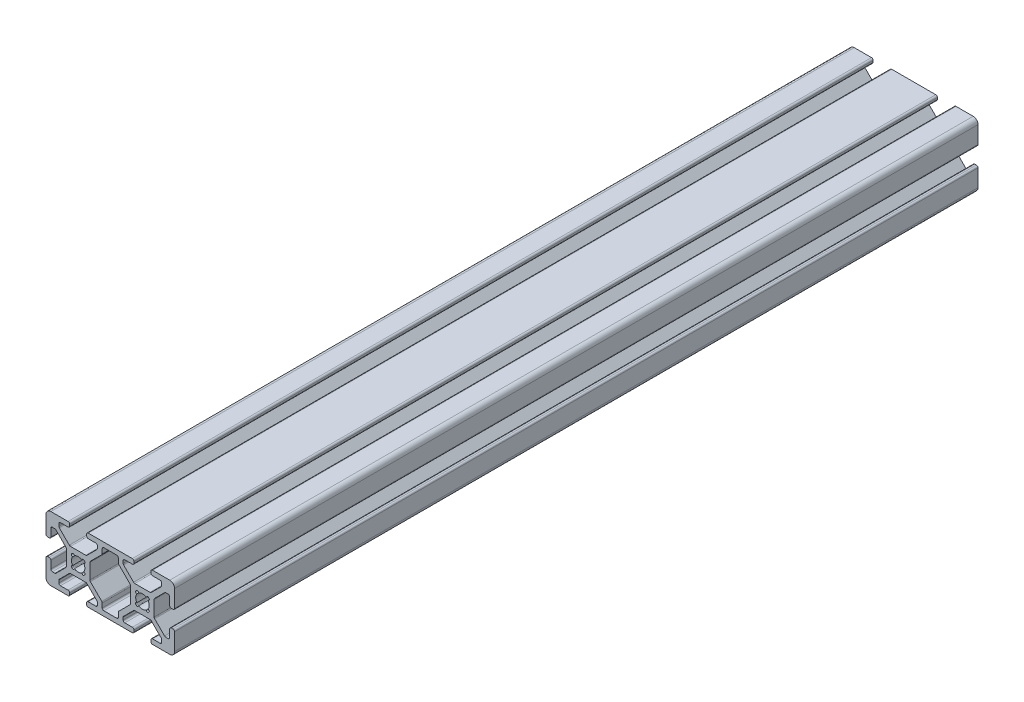
SolidWorks part; units mm, degrees
material "6061-T6 (SS)"
ref_plane "Front Plane" through (0, 0, 0) normal (0, 0, 1) x (1, 0, 0)
ref_plane "Top Plane" through (0, 0, 0) normal (0, 1, 0) x (1, 0, 0)
ref_plane "Right Plane" through (0, 0, 0) normal (1, 0, 0) x (0, 0, -1)
sketch "Sketch1" plane through (0, 0, 0) normal (0, 0, 1) x (1, 0, 0)
  line L0 (-20, 8.5) -> (-20, 3.138)
  line L1 (-19.492, 2.63) -> (-19.008, 2.63)
  line L2 (-18.5, 3.138) -> (-18.5, 5.487)
  line L3 (-17.992, 5.995) -> (-17.2661, 5.995)
  line L4 (-16.9069, 5.8462) -> (-13.8038, 2.7431)
  line L5 (-13.655, 2.3839) -> (-13.655, -2.3839)
  line L6 (-18.5, 10) -> (-13.138, 10)
  line L7 (-12.63, 9.492) -> (-12.63, 9.008)
  line L8 (-13.138, 8.5) -> (-15.487, 8.5)
  line L9 (-15.995, 7.992) -> (-15.995, 7.2661)
  line L10 (-15.8462, 6.9069) -> (-12.7431, 3.8038)
  line L11 (-12.3839, 3.655) -> (-7.6161, 3.655)
  line L12 (-20, 10) -> (-10, 0) construction
  line L13 (-10, 0) -> (-6.345, 0) construction
  line L14 (-13.655, 0) -> (-10, 0) construction
  line L15 (-10, -3.655) -> (-10, 0) construction
  line L16 (-11.7504, 1.5704) -> (-11.5704, 1.7504) construction
  line L17 (-12.0287, 1.8487) -> (-11.8487, 2.0287)
  line L18 (-16.9069, 5.8462) -> (-15.8462, 6.9069) construction
  line L19 (-7.9713, 1.8487) -> (-8.1513, 2.0287)
  line L20 (-7.37, 9.492) -> (-7.37, 9.008)
  line L21 (-6.862, 8.5) -> (-4.513, 8.5)
  line L22 (-4.005, 7.992) -> (-4.005, 7.2661)
  line L23 (-4.1538, 6.9069) -> (-7.2569, 3.8038)
  line L24 (-6.862, 10) -> (6.862, 10)
  line L25 (0, 10) -> (0, -10) construction
  line L26 (1.997, 8.5) -> (-1.997, 8.5)
  line L27 (-2.505, 7.992) -> (-2.505, 6.6448)
  line L28 (-2.6538, 6.2856) -> (-6.1962, 2.7431)
  line L29 (-6.345, 2.3839) -> (-6.345, -2.3839)
  line L30 (-6.345, 0) -> (6.345, 0) construction
  line L31 (-4.005, 7.629) -> (-2.505, 7.629) construction
  line L32 (-5.7053, 5.3553) -> (-4.6447, 4.2947) construction
  line L33 (5.7053, 5.3553) -> (4.6447, 4.2947) construction
  line L34 (4.005, 7.629) -> (2.505, 7.629) construction
  line L35 (16.9069, 5.8462) -> (15.8462, 6.9069) construction
  line L36 (11.7504, 1.5704) -> (11.5704, 1.7504) construction
  line L37 (10, -3.655) -> (10, 3.655) construction
  line L38 (13.655, 0) -> (10, 0) construction
  line L39 (10, 0) -> (6.345, 0) construction
  line L40 (20, 10) -> (10, 0) construction
  line L41 (6.345, 2.3839) -> (6.345, -2.3839)
  line L42 (2.6538, 6.2856) -> (6.1962, 2.7431)
  line L43 (2.505, 7.992) -> (2.505, 6.6448)
  line L44 (4.1538, 6.9069) -> (7.2569, 3.8038)
  line L45 (4.005, 7.992) -> (4.005, 7.2661)
  line L46 (6.862, 8.5) -> (4.513, 8.5)
  line L47 (7.37, 9.492) -> (7.37, 9.008)
  line L48 (7.9713, 1.8487) -> (8.1513, 2.0287)
  line L49 (12.0287, 1.8487) -> (11.8487, 2.0287)
  line L50 (12.3839, 3.655) -> (7.6161, 3.655)
  line L51 (15.8462, 6.9069) -> (12.7431, 3.8038)
  line L52 (15.995, 7.992) -> (15.995, 7.2661)
  line L53 (13.138, 8.5) -> (15.487, 8.5)
  line L54 (12.63, 9.492) -> (12.63, 9.008)
  line L55 (18.5, 10) -> (13.138, 10)
  line L56 (13.655, 2.3839) -> (13.655, -2.3839)
  line L57 (16.9069, 5.8462) -> (13.8038, 2.7431)
  line L58 (17.992, 5.995) -> (17.2661, 5.995)
  line L59 (18.5, 3.138) -> (18.5, 5.487)
  line L60 (19.492, 2.63) -> (19.008, 2.63)
  line L61 (20, 8.5) -> (20, 3.138)
  line L62 (-10, 0) -> (-10, 3.655) construction
  line L63 (11.7504, -1.5704) -> (11.5704, -1.7504) construction
  line L65 (4.005, -7.629) -> (2.505, -7.629) construction
  line L68 (-4.005, -7.629) -> (-2.505, -7.629) construction
  line L70 (-11.7504, -1.5704) -> (-11.5704, -1.7504) construction
  line L72 (20, -8.5) -> (20, -3.138)
  line L73 (19.492, -2.63) -> (19.008, -2.63)
  line L74 (18.5, -3.138) -> (18.5, -5.487)
  line L75 (17.992, -5.995) -> (17.2661, -5.995)
  line L76 (16.9069, -5.8462) -> (13.8038, -2.7431)
  line L77 (18.5, -10) -> (13.138, -10)
  line L78 (12.63, -9.492) -> (12.63, -9.008)
  line L79 (13.138, -8.5) -> (15.487, -8.5)
  line L80 (15.995, -7.992) -> (15.995, -7.2661)
  line L81 (15.8462, -6.9069) -> (12.7431, -3.8038)
  line L82 (12.3839, -3.655) -> (7.6161, -3.655)
  line L83 (12.0287, -1.8487) -> (11.8487, -2.0287)
  line L84 (7.9713, -1.8487) -> (8.1513, -2.0287)
  line L85 (7.37, -9.492) -> (7.37, -9.008)
  line L86 (6.862, -8.5) -> (4.513, -8.5)
  line L87 (4.005, -7.992) -> (4.005, -7.2661)
  line L88 (4.1538, -6.9069) -> (7.2569, -3.8038)
  line L89 (2.505, -7.992) -> (2.505, -6.6448)
  line L90 (2.6538, -6.2856) -> (6.1962, -2.7431)
  line L91 (-2.6538, -6.2856) -> (-6.1962, -2.7431)
  line L92 (-2.505, -7.992) -> (-2.505, -6.6448)
  line L93 (1.997, -8.5) -> (-1.997, -8.5)
  line L94 (-6.862, -10) -> (6.862, -10)
  line L95 (-4.1538, -6.9069) -> (-7.2569, -3.8038)
  line L96 (-4.005, -7.992) -> (-4.005, -7.2661)
  line L97 (-6.862, -8.5) -> (-4.513, -8.5)
  line L98 (-7.37, -9.492) -> (-7.37, -9.008)
  line L99 (-7.9713, -1.8487) -> (-8.1513, -2.0287)
  line L100 (-12.0287, -1.8487) -> (-11.8487, -2.0287)
  line L101 (-12.3839, -3.655) -> (-7.6161, -3.655)
  line L102 (-15.8462, -6.9069) -> (-12.7431, -3.8038)
  line L103 (-15.995, -7.992) -> (-15.995, -7.2661)
  line L104 (-13.138, -8.5) -> (-15.487, -8.5)
  line L105 (-12.63, -9.492) -> (-12.63, -9.008)
  line L106 (-18.5, -10) -> (-13.138, -10)
  line L107 (-16.9069, -5.8462) -> (-13.8038, -2.7431)
  line L108 (-17.992, -5.995) -> (-17.2661, -5.995)
  line L109 (-18.5, -3.138) -> (-18.5, -5.487)
  line L110 (-19.492, -2.63) -> (-19.008, -2.63)
  line L111 (-20, -8.5) -> (-20, -3.138)
  arc A0 (-20, 8.5) -> (-18.5, 10) centre (-18.5, 8.5) cw
  arc A1 (-13.8038, 2.7431) -> (-13.655, 2.3839) centre (-14.163, 2.3839) cw
  arc A2 (-17.2661, 5.995) -> (-16.9069, 5.8462) centre (-17.2661, 5.487) cw
  arc A3 (-18.5, 5.487) -> (-17.992, 5.995) centre (-17.992, 5.487) cw
  arc A4 (-19.008, 2.63) -> (-18.5, 3.138) centre (-19.008, 3.138) ccw
  arc A5 (-20, 3.138) -> (-19.492, 2.63) centre (-19.492, 3.138) ccw
  arc A6 (-13.138, 10) -> (-12.63, 9.492) centre (-13.138, 9.492) cw
  arc A7 (-12.63, 9.008) -> (-13.138, 8.5) centre (-13.138, 9.008) cw
  arc A8 (-15.487, 8.5) -> (-15.995, 7.992) centre (-15.487, 7.992) ccw
  arc A9 (-15.995, 7.2661) -> (-15.8462, 6.9069) centre (-15.487, 7.2661) ccw
  arc A10 (-12.7431, 3.8038) -> (-12.3839, 3.655) centre (-12.3839, 4.163) ccw
  arc A11 (-8.8227, 1.7341) -> (-11.1773, 1.7341) centre (-10, 0) ccw
  arc A12 (-12.0287, 1.8487) -> (-11.7341, 1.1773) centre (-11.7504, 1.5704) ccw
  arc A13 (-11.1773, 1.7341) -> (-11.8487, 2.0287) centre (-11.5704, 1.7504) ccw
  arc A14 (-11.7341, 1.1773) -> (-11.7341, -1.1773) centre (-10, 0) ccw
  arc A15 (-8.2659, 1.1773) -> (-8.2659, -1.1773) centre (-10, 0) cw
  arc A16 (-7.9713, 1.8487) -> (-8.2659, 1.1773) centre (-8.2496, 1.5704) cw
  arc A17 (-8.8227, 1.7341) -> (-8.1513, 2.0287) centre (-8.4296, 1.7504) cw
  arc A18 (-6.862, 10) -> (-7.37, 9.492) centre (-6.862, 9.492) ccw
  arc A19 (-7.37, 9.008) -> (-6.862, 8.5) centre (-6.862, 9.008) ccw
  arc A20 (-4.513, 8.5) -> (-4.005, 7.992) centre (-4.513, 7.992) cw
  arc A21 (-4.005, 7.2661) -> (-4.1538, 6.9069) centre (-4.513, 7.2661) cw
  arc A22 (-7.2569, 3.8038) -> (-7.6161, 3.655) centre (-7.6161, 4.163) cw
  arc A23 (-1.997, 8.5) -> (-2.505, 7.992) centre (-1.997, 7.992) ccw
  arc A24 (-2.505, 6.6448) -> (-2.6538, 6.2856) centre (-3.013, 6.6448) cw
  arc A25 (-6.1962, 2.7431) -> (-6.345, 2.3839) centre (-5.837, 2.3839) ccw
  arc A26 (6.1962, 2.7431) -> (6.345, 2.3839) centre (5.837, 2.3839) cw
  arc A27 (2.505, 6.6448) -> (2.6538, 6.2856) centre (3.013, 6.6448) ccw
  arc A28 (1.997, 8.5) -> (2.505, 7.992) centre (1.997, 7.992) cw
  arc A29 (7.2569, 3.8038) -> (7.6161, 3.655) centre (7.6161, 4.163) ccw
  arc A30 (4.005, 7.2661) -> (4.1538, 6.9069) centre (4.513, 7.2661) ccw
  arc A31 (4.513, 8.5) -> (4.005, 7.992) centre (4.513, 7.992) ccw
  arc A32 (7.37, 9.008) -> (6.862, 8.5) centre (6.862, 9.008) cw
  arc A33 (6.862, 10) -> (7.37, 9.492) centre (6.862, 9.492) cw
  arc A34 (8.8227, 1.7341) -> (8.1513, 2.0287) centre (8.4296, 1.7504) ccw
  arc A35 (7.9713, 1.8487) -> (8.2659, 1.1773) centre (8.2496, 1.5704) ccw
  arc A36 (8.2659, 1.1773) -> (8.2659, -1.1773) centre (10, 0) ccw
  arc A37 (11.7341, 1.1773) -> (11.7341, -1.1773) centre (10, 0) cw
  arc A38 (11.1773, 1.7341) -> (11.8487, 2.0287) centre (11.5704, 1.7504) cw
  arc A39 (12.0287, 1.8487) -> (11.7341, 1.1773) centre (11.7504, 1.5704) cw
  arc A40 (8.8227, 1.7341) -> (11.1773, 1.7341) centre (10, 0) cw
  arc A41 (12.7431, 3.8038) -> (12.3839, 3.655) centre (12.3839, 4.163) cw
  arc A42 (15.995, 7.2661) -> (15.8462, 6.9069) centre (15.487, 7.2661) cw
  arc A43 (15.487, 8.5) -> (15.995, 7.992) centre (15.487, 7.992) cw
  arc A44 (12.63, 9.008) -> (13.138, 8.5) centre (13.138, 9.008) ccw
  arc A45 (13.138, 10) -> (12.63, 9.492) centre (13.138, 9.492) ccw
  arc A46 (20, 3.138) -> (19.492, 2.63) centre (19.492, 3.138) cw
  arc A47 (19.008, 2.63) -> (18.5, 3.138) centre (19.008, 3.138) cw
  arc A48 (18.5, 5.487) -> (17.992, 5.995) centre (17.992, 5.487) ccw
  arc A49 (17.2661, 5.995) -> (16.9069, 5.8462) centre (17.2661, 5.487) ccw
  arc A50 (13.8038, 2.7431) -> (13.655, 2.3839) centre (14.163, 2.3839) ccw
  arc A51 (20, 8.5) -> (18.5, 10) centre (18.5, 8.5) ccw
  arc A52 (20, -8.5) -> (18.5, -10) centre (18.5, -8.5) cw
  arc A53 (13.8038, -2.7431) -> (13.655, -2.3839) centre (14.163, -2.3839) cw
  arc A54 (17.2661, -5.995) -> (16.9069, -5.8462) centre (17.2661, -5.487) cw
  arc A55 (18.5, -5.487) -> (17.992, -5.995) centre (17.992, -5.487) cw
  arc A56 (19.008, -2.63) -> (18.5, -3.138) centre (19.008, -3.138) ccw
  arc A57 (20, -3.138) -> (19.492, -2.63) centre (19.492, -3.138) ccw
  arc A58 (13.138, -10) -> (12.63, -9.492) centre (13.138, -9.492) cw
  arc A59 (12.63, -9.008) -> (13.138, -8.5) centre (13.138, -9.008) cw
  arc A60 (15.487, -8.5) -> (15.995, -7.992) centre (15.487, -7.992) ccw
  arc A61 (15.995, -7.2661) -> (15.8462, -6.9069) centre (15.487, -7.2661) ccw
  arc A62 (12.7431, -3.8038) -> (12.3839, -3.655) centre (12.3839, -4.163) ccw
  arc A63 (8.8227, -1.7341) -> (11.1773, -1.7341) centre (10, 0) ccw
  arc A64 (12.0287, -1.8487) -> (11.7341, -1.1773) centre (11.7504, -1.5704) ccw
  arc A65 (11.1773, -1.7341) -> (11.8487, -2.0287) centre (11.5704, -1.7504) ccw
  arc A66 (7.9713, -1.8487) -> (8.2659, -1.1773) centre (8.2496, -1.5704) cw
  arc A67 (8.8227, -1.7341) -> (8.1513, -2.0287) centre (8.4296, -1.7504) cw
  arc A68 (6.862, -10) -> (7.37, -9.492) centre (6.862, -9.492) ccw
  arc A69 (7.37, -9.008) -> (6.862, -8.5) centre (6.862, -9.008) ccw
  arc A70 (4.513, -8.5) -> (4.005, -7.992) centre (4.513, -7.992) cw
  arc A71 (4.005, -7.2661) -> (4.1538, -6.9069) centre (4.513, -7.2661) cw
  arc A72 (7.2569, -3.8038) -> (7.6161, -3.655) centre (7.6161, -4.163) cw
  arc A73 (1.997, -8.5) -> (2.505, -7.992) centre (1.997, -7.992) ccw
  arc A74 (2.505, -6.6448) -> (2.6538, -6.2856) centre (3.013, -6.6448) cw
  arc A75 (6.1962, -2.7431) -> (6.345, -2.3839) centre (5.837, -2.3839) ccw
  arc A76 (-6.1962, -2.7431) -> (-6.345, -2.3839) centre (-5.837, -2.3839) cw
  arc A77 (-2.505, -6.6448) -> (-2.6538, -6.2856) centre (-3.013, -6.6448) ccw
  arc A78 (-1.997, -8.5) -> (-2.505, -7.992) centre (-1.997, -7.992) cw
  arc A79 (-7.2569, -3.8038) -> (-7.6161, -3.655) centre (-7.6161, -4.163) ccw
  arc A80 (-4.005, -7.2661) -> (-4.1538, -6.9069) centre (-4.513, -7.2661) ccw
  arc A81 (-4.513, -8.5) -> (-4.005, -7.992) centre (-4.513, -7.992) ccw
  arc A82 (-7.37, -9.008) -> (-6.862, -8.5) centre (-6.862, -9.008) cw
  arc A83 (-6.862, -10) -> (-7.37, -9.492) centre (-6.862, -9.492) cw
  arc A84 (-8.8227, -1.7341) -> (-8.1513, -2.0287) centre (-8.4296, -1.7504) ccw
  arc A85 (-7.9713, -1.8487) -> (-8.2659, -1.1773) centre (-8.2496, -1.5704) ccw
  arc A86 (-11.1773, -1.7341) -> (-11.8487, -2.0287) centre (-11.5704, -1.7504) cw
  arc A87 (-12.0287, -1.8487) -> (-11.7341, -1.1773) centre (-11.7504, -1.5704) cw
  arc A88 (-8.8227, -1.7341) -> (-11.1773, -1.7341) centre (-10, 0) cw
  arc A89 (-12.7431, -3.8038) -> (-12.3839, -3.655) centre (-12.3839, -4.163) cw
  arc A90 (-15.995, -7.2661) -> (-15.8462, -6.9069) centre (-15.487, -7.2661) cw
  arc A91 (-15.487, -8.5) -> (-15.995, -7.992) centre (-15.487, -7.992) cw
  arc A92 (-12.63, -9.008) -> (-13.138, -8.5) centre (-13.138, -9.008) ccw
  arc A93 (-13.138, -10) -> (-12.63, -9.492) centre (-13.138, -9.492) ccw
  arc A94 (-20, -3.138) -> (-19.492, -2.63) centre (-19.492, -3.138) cw
  arc A95 (-19.008, -2.63) -> (-18.5, -3.138) centre (-19.008, -3.138) cw
  arc A96 (-18.5, -5.487) -> (-17.992, -5.995) centre (-17.992, -5.487) ccw
  arc A97 (-17.2661, -5.995) -> (-16.9069, -5.8462) centre (-17.2661, -5.487) ccw
  arc A98 (-13.8038, -2.7431) -> (-13.655, -2.3839) centre (-14.163, -2.3839) ccw
  arc A99 (-20, -8.5) -> (-18.5, -10) centre (-18.5, -8.5) ccw
  point P18 (-16.3765, 6.3765)
  point P46 (-11.6604, 1.6604)
  point P72 (-10, -0.3279)
  point P166 (0, 8.5)
  point P175 (-10, -0.0093)
  point P181 (0, 0)
  point P313 (0, -8.5)
  dimension "D8" = 1.5
  dimension "D9" = 0.508
  dimension "D11" = 0.787
  dimension "D12" = 2.096
  dimension "D1" = 10
  dimension "D2" = 1.5
  dimension "D3" = 4.845
  dimension "D4" = 1.5
  dimension "D5" = 5.995
  dimension "D6" = 2.63
  dimension "D7" = 20
  dimension "D10" = 2.3482
  dimension "D13" = 0.2546
extrude "Boss-Extrude1" add sketch "Sketch1" along normal mid plane 250
